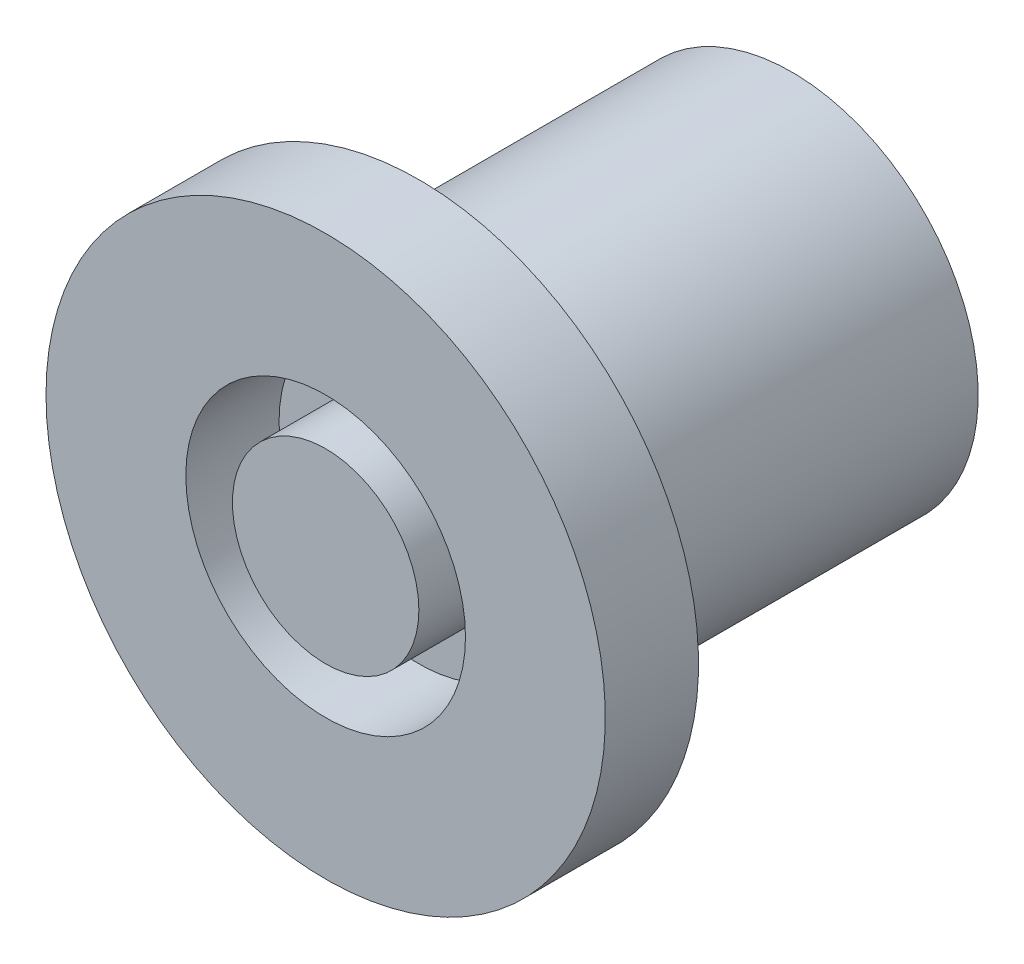
SolidWorks part; units mm, degrees
ref_plane "Front Plane" through (0, 0, 0) normal (0, 0, 1) x (1, 0, 0)
ref_plane "Top Plane" through (0, 0, 0) normal (0, 1, 0) x (1, 0, 0)
ref_plane "Right Plane" through (0, 0, 0) normal (1, 0, 0) x (0, 0, -1)
sketch "Sketch1" plane through (0, 0, 0) normal (0, 0, 1) x (1, 0, 0)
  circle A0 centre (0, 0) radius 1
extrude "Boss-Extrude1" add sketch "Sketch1" along normal blind 2
sketch "Sketch2" plane through (0, 0, 2) normal (0, 0, 1) x (1, 0, 0)
  circle A2 centre (0, 0) radius 1.5
extrude "Boss-Extrude2" add sketch "Sketch2" along normal blind 0.5
sketch "Sketch3" plane through (0, 0, 2.5) normal (0, 0, 1) x (1, 0, 0)
  circle A0 centre (0, 0) radius 0.5
  circle A1 centre (0, 0) radius 0.75
extrude "Cut-Extrude1" cut sketch "Sketch3" against normal blind 0.5
